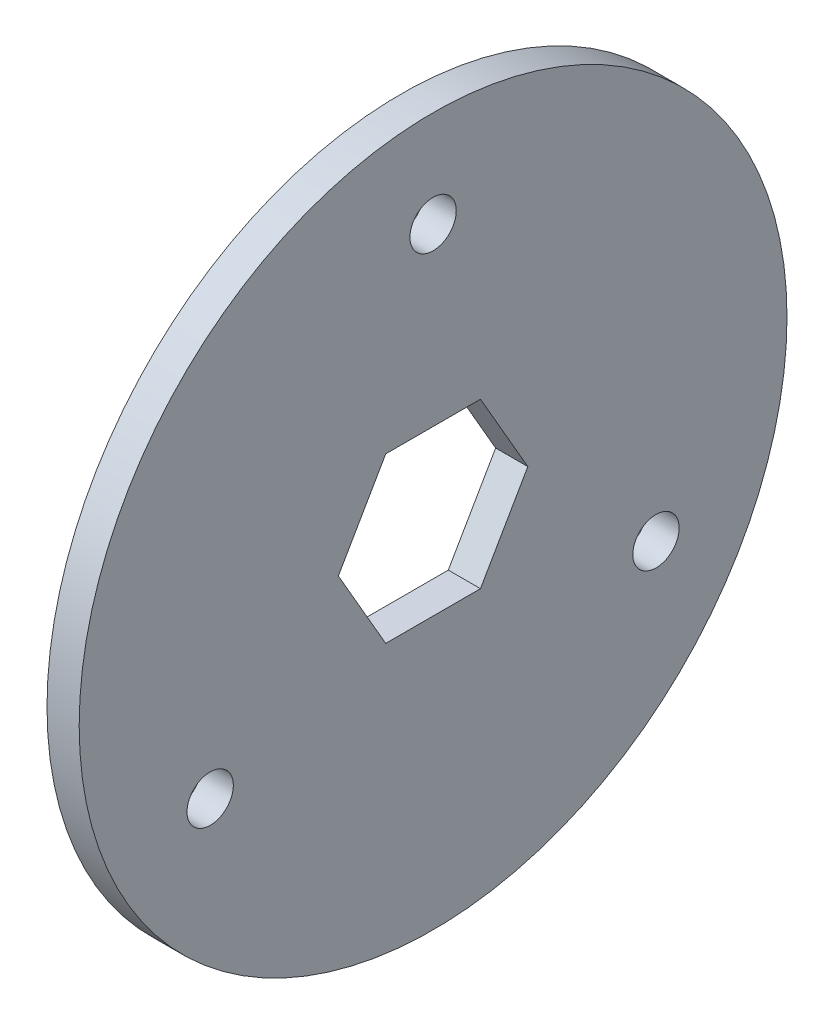
SolidWorks part; units mm, degrees
ref_plane "Front Plane" through (0, 0, 0) normal (0, 0, 1) x (1, 0, 0)
ref_plane "Top Plane" through (0, 0, 0) normal (0, 1, 0) x (1, 0, 0)
ref_plane "Right Plane" through (0, 0, 0) normal (1, 0, 0) x (0, 0, -1)
sketch "Sketch1" plane through (0, 0, 0) normal (1, 0, 0) x (0, 0, -1)
  line L0 (0, 0) -> (0, 20) construction
  line L7 (0, 0) -> (17.3205, -10) construction
  line L8 (0, 0) -> (-17.3205, -10) construction
  line L14 (3.6806, 6.375) -> (-3.6806, 6.375)
  line L15 (-3.6806, 6.375) -> (-7.3612, 0)
  line L16 (-7.3612, 0) -> (-3.6806, -6.375)
  line L17 (-3.6806, -6.375) -> (3.6806, -6.375)
  line L18 (3.6806, -6.375) -> (7.3612, 0)
  line L19 (7.3612, 0) -> (3.6806, 6.375)
  circle A0 centre (0, 0) radius 27.5
  circle A4 centre (0, 0) radius 20 construction
  circle A5 centre (0, 20) radius 1.8
  circle A6 centre (-17.3205, -10) radius 1.8
  circle A7 centre (17.3205, -10) radius 1.8
  circle A9 centre (0, 0) radius 6.375 construction
  point P4 (0, 6.375)
  dimension "D1" = 55
  dimension "D5" = 120
  dimension "D3" = 40
  dimension "D4" = 3.6
  dimension "D2" = 12.75
  dimension "D6" = 120
extrude "Boss-Extrude1" add sketch "Sketch1" along normal blind 2.5
